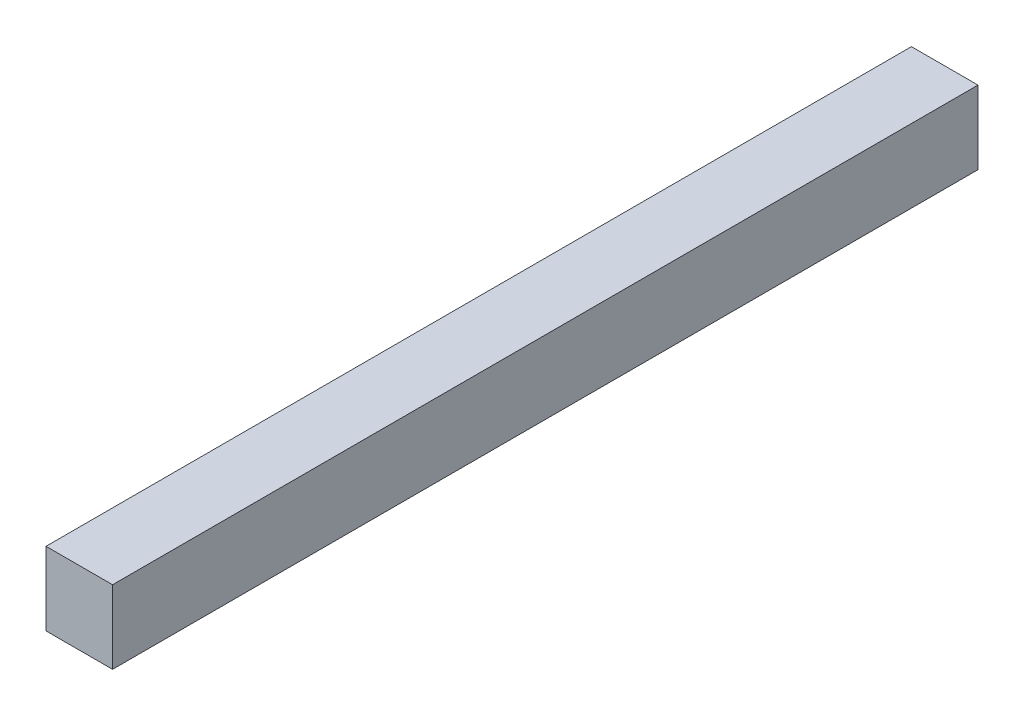
SolidWorks part; units mm, degrees
material "AISI 1045 Steel, cold drawn"
ref_plane "Front Plane" through (0, 0, 0) normal (0, 0, 1) x (1, 0, 0)
ref_plane "Top Plane" through (0, 0, 0) normal (0, 1, 0) x (1, 0, 0)
ref_plane "Right Plane" through (0, 0, 0) normal (1, 0, 0) x (0, 0, -1)
sketch "Sketch2" plane through (0, 0, 0) normal (0, 0, 1) x (1, 0, 0)
  line L1 (-10, 11.01) -> (10, 11.01)
  line L2 (-10, 11.01) -> (-10, -11.01)
  line L3 (-10, -11.01) -> (10, -11.01)
  line L4 (10, 11.01) -> (10, -11.01)
  line L5 (0, -11.01) -> (0, 11.01) construction
  line L6 (-10, 0) -> (10, 0) construction
  point P0 (0, 0)
  dimension "D1" = 20
  dimension "D2" = 22.02
extrude "Boss-Extrude1" add sketch "Sketch2" along normal blind 260 contours L2 L3 L4 L1
